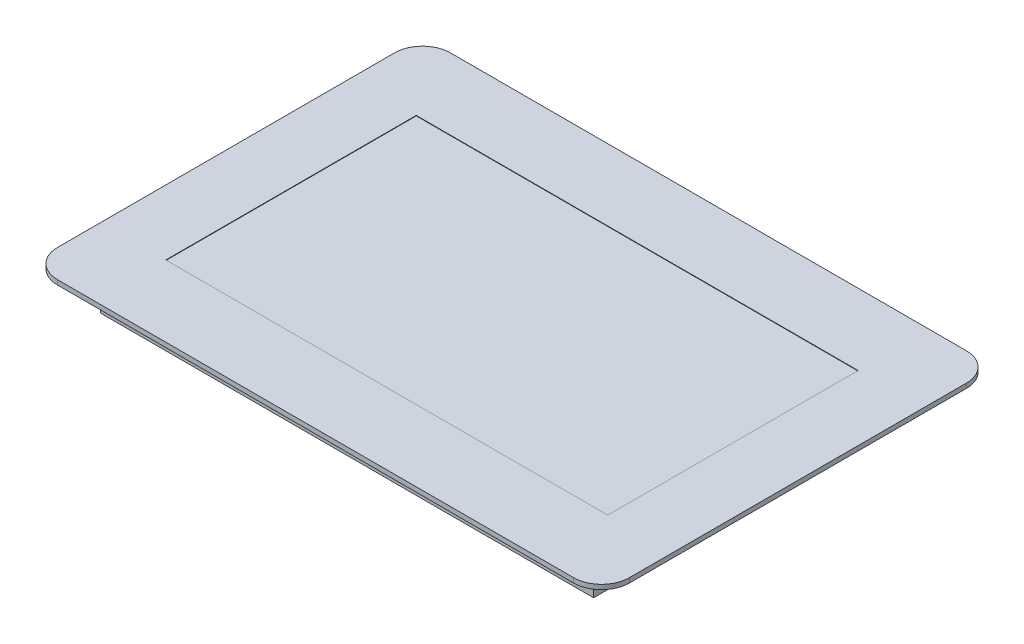
SolidWorks part; units mm, degrees
ref_plane "Front Plane" through (0, 0, 0) normal (0, 0, 1) x (1, 0, 0)
ref_plane "Top Plane" through (0, 0, 0) normal (0, 1, 0) x (1, 0, 0)
ref_plane "Right Plane" through (0, 0, 0) normal (1, 0, 0) x (0, 0, -1)
sketch "Sketch2" plane through (0, 0, 0) normal (0, 1, 0) x (1, 0, 0)
  line L1 (-53, 33.85) -> (53, 33.85)
  line L2 (-53, 33.85) -> (-53, -33.85)
  line L3 (-53, -33.85) -> (53, -33.85)
  line L4 (53, 33.85) -> (53, -33.85)
  line L5 (-53, 33.85) -> (53, -33.85) construction
  line L6 (-53, -33.85) -> (53, 33.85) construction
  point P0 (0, 0)
  dimension "D1" = 106
  dimension "D2" = 67.7
extrude "Boss-Extrude1" add sketch "Sketch2" along normal blind 8.4
sketch "Sketch3" plane through (0, 8.4, 0) normal (0, 1, 0) x (1, 0, 0)
  line L0 (0, 0) -> (0, 1.6) construction
  line L1 (-55.5, 43.85) -> (55.5, 43.85)
  line L2 (-61.5, 37.85) -> (-61.5, -34.65)
  line L3 (-55.5, -40.65) -> (55.5, -40.65)
  line L4 (61.5, 37.85) -> (61.5, -34.65)
  line L5 (-61.5, 43.85) -> (61.5, -40.65) construction
  line L6 (-61.5, -40.65) -> (61.5, 43.85) construction
  line L7 (53, 33.85) -> (-53, 33.85) construction
  arc A0 (-61.5, -34.65) -> (-55.5, -40.65) centre (-55.5, -34.65) ccw
  arc A1 (-55.5, 43.85) -> (-61.5, 37.85) centre (-55.5, 37.85) ccw
  arc A2 (55.5, 43.85) -> (61.5, 37.85) centre (55.5, 37.85) cw
  arc A3 (55.5, -40.65) -> (61.5, -34.65) centre (55.5, -34.65) ccw
  point P0 (0, 1.6)
  point P8 (0, 0)
  point P9 (0, 0)
  point P12 (73.5906, 43.85)
  point P13 (70.7866, -41.0503)
  dimension "D4" = 6
  dimension "D1" = 10
  dimension "D2" = 123
  dimension "D3" = 84.5
extrude "Boss-Extrude2" add sketch "Sketch3" against normal blind 1
sketch "Sketch5" plane through (0, 8.4, 0) normal (0, 1, 0) x (1, 0, 0)
  line L0 (-61.5, 43.85) -> (61.5, -40.65) construction
  line L1 (-47.52, 28.53) -> (47.52, 28.53)
  line L2 (-47.52, 28.53) -> (-47.52, -25.33)
  line L3 (-47.52, -25.33) -> (47.52, -25.33)
  line L4 (47.52, 28.53) -> (47.52, -25.33)
  line L5 (-47.52, 28.53) -> (47.52, -25.33) construction
  line L6 (-47.52, -25.33) -> (47.52, 28.53) construction
  line L7 (-61.5, -40.65) -> (61.5, 43.85) construction
  point P0 (0, 1.6)
  point P7 (0, 1.6)
  dimension "D1" = 95.04
  dimension "D2" = 53.86
extrude "Cut-Extrude1" cut sketch "Sketch5" against normal blind 0.1
